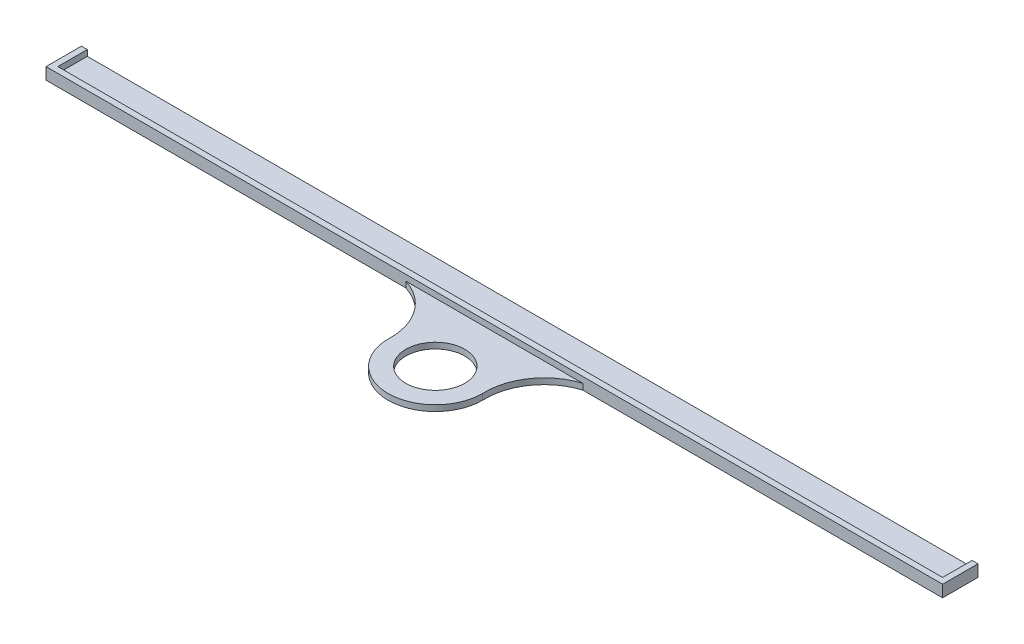
SolidWorks part; units mm, degrees
ref_plane "Front Plane" through (0, 0, 0) normal (0, 0, 1) x (1, 0, 0)
ref_plane "Top Plane" through (0, 0, 0) normal (0, 1, 0) x (1, 0, 0)
ref_plane "Right Plane" through (0, 0, 0) normal (1, 0, 0) x (0, 0, -1)
sketch "Sketch2" plane through (0, 0, 0) normal (0, 1, 0) x (1, 0, 0)
  line L0 (-152, 6) -> (152, -6) construction
  line L1 (-152, -6) -> (152, -6)
  line L2 (-152, -6) -> (-152, 6)
  line L3 (-152, 6) -> (152, 6)
  line L4 (152, -6) -> (152, 6)
  line L5 (0, -6) -> (0, 6) construction
  line L6 (-30, -26) -> (30, -26) construction
  line L7 (-30, -6) -> (30, -6)
  line L8 (-30, -6) -> (-30, -46) construction
  line L9 (-30, -46) -> (30, -46) construction
  line L10 (30, -6) -> (30, -46) construction
  line L11 (0, -46) -> (0, -6) construction
  circle A0 centre (0, -26) radius 10
  circle A1 centre (0, -26) radius 16
  arc A2 (-30, -6) -> (-16, -26) centre (-35.9791, -25.0854) cw
  arc A3 (16, -26) -> (30, -6) centre (35.9791, -25.0854) cw
  point P6 (0, 0)
  dimension "D6" = 20
  dimension "D7" = 32
  dimension "D8" = 20
  dimension "D9" = 20
  dimension "D1" = 12
  dimension "D2" = 304
  dimension "D3" = 30
  dimension "D4" = 60
  dimension "D5" = 40
extrude "Boss-Extrude2" add sketch "Sketch2" against normal blind 2 contours L1 L4 L3 L2 | A1 A3 L1 A2 | A1 A3 A2 A0
sketch "Sketch4" plane through (0, 0, 0) normal (0, 1, 0) x (1, 0, 0)
  line L0 (-152, 6) -> (-152, -6)
  line L1 (-152, -6) -> (152, -6)
  line L2 (152, -6) -> (152, 6)
  line L3 (0, 6) -> (0, -6) construction
  line L4 (-152, 6) -> (152, 6) construction
  line L5 (-150, 6) -> (-150, -6)
  line L6 (150, 6) -> (150, -6)
  line L7 (-152, -4) -> (152, -4)
  line L8 (-150, 6) -> (-152, 6)
  line L9 (152, 6) -> (150, 6)
  line M4 (-152, -6) -> (-30, -6)
  line M8 (30, -6) -> (152, -6)
  line M9 (152, -6) -> (152, 6)
  line M10 (152, 6) -> (-152, 6)
  line M11 (-152, 6) -> (-152, -6)
  dimension "D1" = 2
  dimension "D2" = 2
extrude "Boss-Extrude4" add sketch "Sketch4" along normal blind 2 contours L7 L5 M11 M10 | L7 L0 L5 M4 | L3 L7 L5 L1 | L7 L3 L1 L6 M8 | L7 L6 L1 M9 | L6 L7 L2 M10
